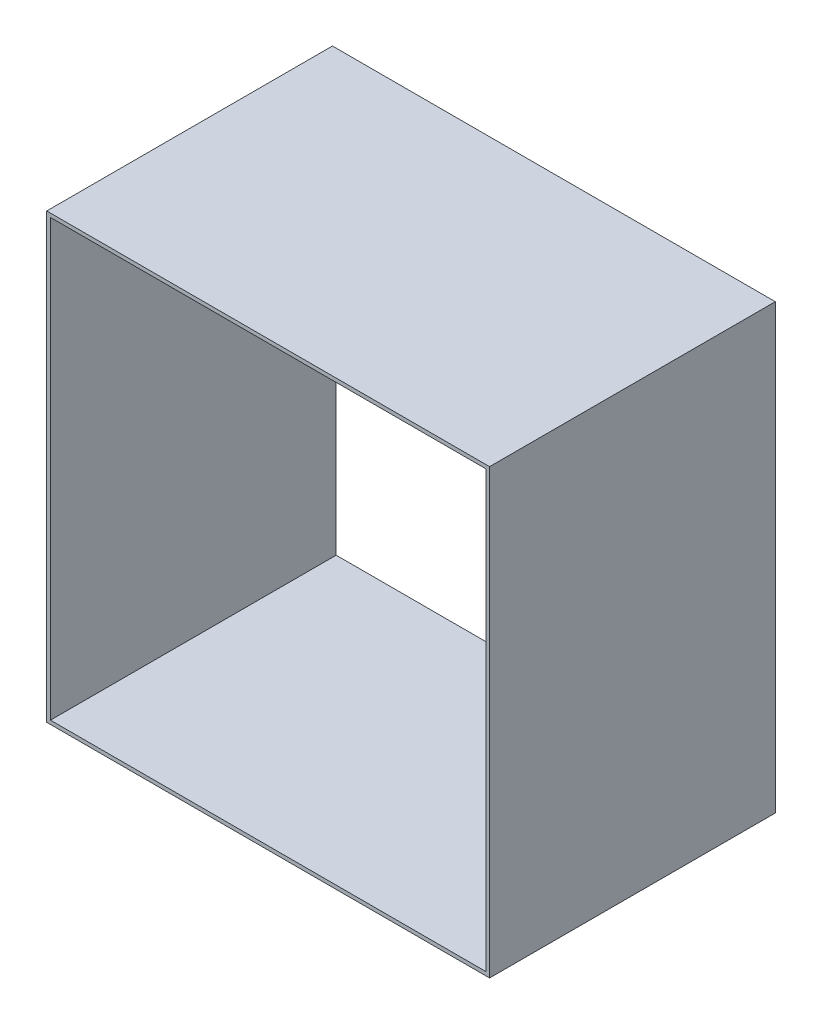
SolidWorks part; units mm, degrees
material "Beech"
ref_plane "Front Plane" through (0, 0, 0) normal (0, 0, 1) x (1, 0, 0)
ref_plane "Top Plane" through (0, 0, 0) normal (0, 1, 0) x (1, 0, 0)
ref_plane "Right Plane" through (0, 0, 0) normal (1, 0, 0) x (0, 0, -1)
sketch "Sketch1" plane through (0, 0, 0) normal (0, 0, 1) x (1, 0, 0)
  line L1 (-320, -320) -> (320, -320)
  line L2 (-320, -320) -> (-320, 320)
  line L3 (-320, 320) -> (320, 320)
  line L4 (320, -320) -> (320, 320)
  line L5 (-320, -320) -> (320, 320) construction
  line L6 (-320, 320) -> (320, -320) construction
  line L7 (-325.5, -325.5) -> (325.5, -325.5)
  line L8 (-325.5, -325.5) -> (-325.5, 325.5)
  line L9 (-325.5, 325.5) -> (325.5, 325.5)
  line L10 (325.5, -325.5) -> (325.5, 325.5)
  line L11 (-325.5, -325.5) -> (325.5, 325.5) construction
  line L12 (-325.5, 325.5) -> (325.5, -325.5) construction
  point P0 (0, 0)
  point P5 (0, 0)
  point P6 (0, 0)
  dimension "D1" = 640
  dimension "D2" = 5.5
extrude "Boss-Extrude1" add sketch "Sketch1" along normal blind 420
